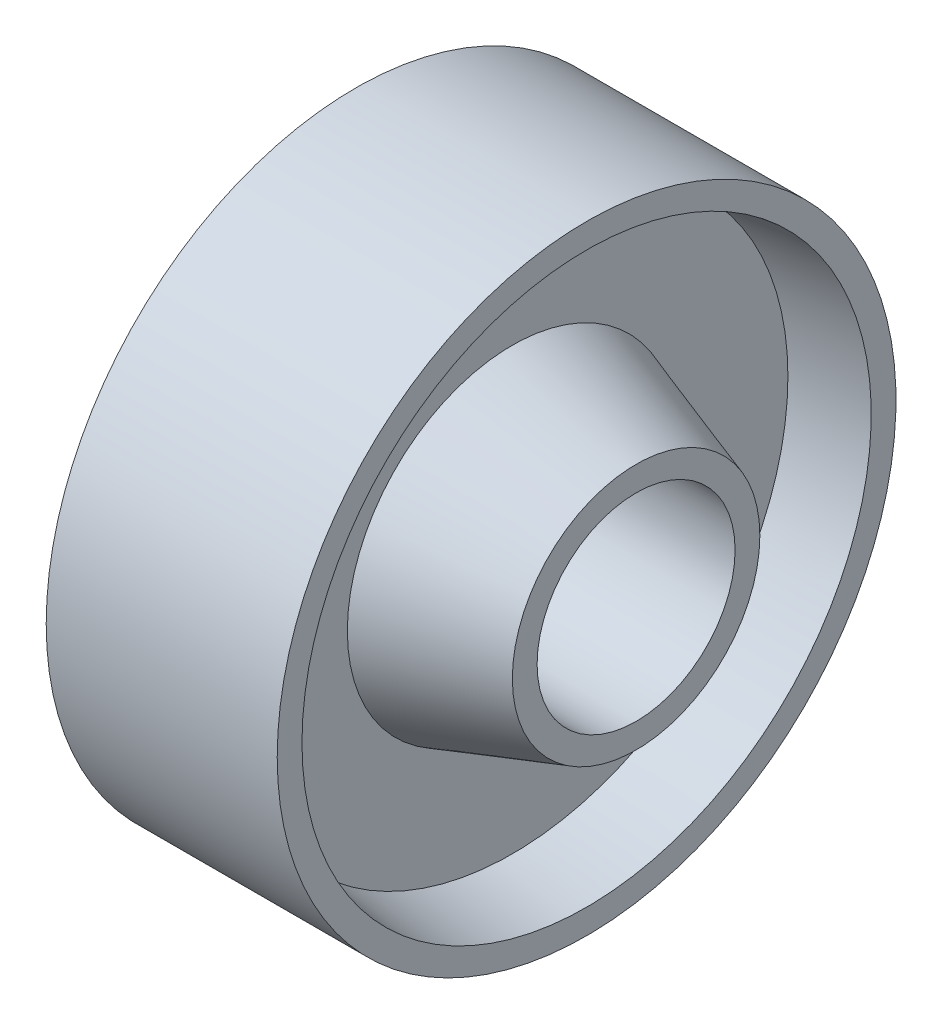
SolidWorks part; units mm, degrees
ref_plane "Front Plane" through (0, 0, 0) normal (0, 0, 1) x (1, 0, 0)
ref_plane "Top Plane" through (0, 0, 0) normal (0, 1, 0) x (1, 0, 0)
ref_plane "Right Plane" through (0, 0, 0) normal (1, 0, 0) x (0, 0, -1)
sketch "Sketch2" plane through (0, 0, 0) normal (0, 0, 1) x (1, 0, 0)
  line L0 (-33.6582, 0) -> (33.6582, 0)
  line L6 (-20, 12) -> (20, 12)
  line L8 (-5, 20) -> (5, 20)
  line L9 (-5, 33.4022) -> (5, 33.4022)
  line L11 (-14, 37.5) -> (14, 37.5)
  line L12 (-14, 37.5) -> (-14, 34.5)
  line L13 (-14, 34.5) -> (-5, 33.4022)
  line L14 (-5, 33.4022) -> (-5, 20)
  line L15 (-5, 20) -> (-20, 15)
  line L16 (-20, 15) -> (-20, 12)
  line L17 (14, 37.5) -> (14, 34.5)
  line L18 (14, 34.5) -> (5, 33.4022)
  line L19 (5, 33.4022) -> (5, 20)
  line L20 (5, 20) -> (20, 15)
  line L21 (20, 15) -> (20, 12)
  point P4 (0, 0)
  point P10 (0, 12)
  point P14 (0, 15)
  point P17 (0, 20)
  point P18 (0, 20)
  point P22 (0, 33.4022)
  point P24 (0, 34.5)
  point P27 (0, 37.5)
revolve "Revolve1" add sketch "Sketch2" angle 360 about L0
